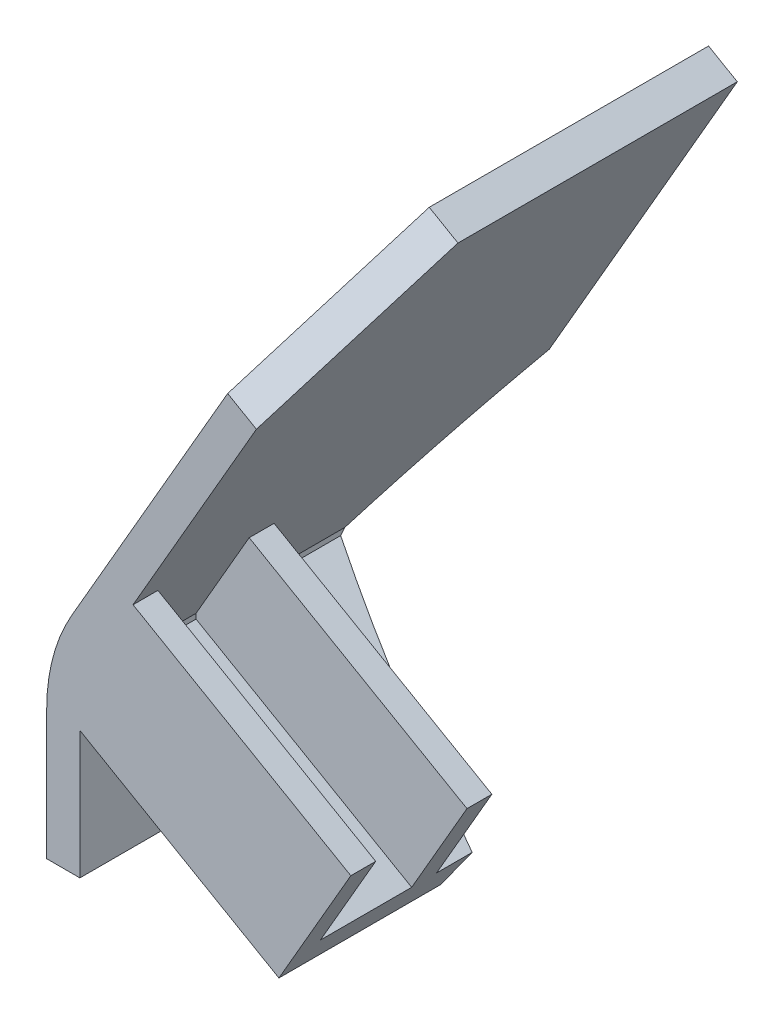
SolidWorks part; units mm, degrees
ref_plane "Alzado" through (0, 0, 0) normal (0, 0, 1) x (1, 0, 0)
ref_plane "Planta" through (0, 0, 0) normal (0, 1, 0) x (1, 0, 0)
ref_plane "Vista lateral" through (0, 0, 0) normal (1, 0, 0) x (0, 0, -1)
sketch "Croquis1" plane through (0, 0, 0) normal (0, 0, 1) x (1, 0, 0)
  line L0 (-23.0092, -16.2678) -> (-23.0092, 0)
  line L1 (-23.0092, 0) -> (5.7228, 49.7654)
  line L9 (-20.0092, -0.8038) -> (7.4549, 46.7654)
  line L16 (-20.0092, -16.2678) -> (-20.0092, -0.8038)
  line L17 (2.2587, 55.7654) -> (-29.0092, 1.6077) construction
  line L18 (26.9908, 55.7654) -> (2.2587, 55.7654) construction
  line L19 (26.9908, 46.7654) -> (26.9908, 55.7654) construction
  line L20 (-29.0092, 1.6077) -> (-29.0092, -70.1962) construction
  line L21 (-29.0092, -70.1962) -> (-20.0092, -70.1962) construction
  line L22 (-20.0092, -16.2678) -> (-23.0092, -16.2678)
  line L23 (-26.0092, 0.8038) -> (-26.0092, -67.1962) construction
  line L24 (-23.0092, -67.1962) -> (-23.0092, 0) construction
  line L25 (-20.0092, -70.1962) -> (-20.0092, -0.8038) construction
  line L26 (-26.0092, -67.1962) -> (-23.0092, -67.1962) construction
  line L27 (3.9908, 52.7654) -> (-26.0092, 0.8038) construction
  line L28 (23.9908, 52.7654) -> (3.9908, 52.7654) construction
  line L29 (23.9908, 49.7654) -> (23.9908, 52.7654) construction
  line L30 (7.4549, 46.7654) -> (5.7228, 49.7654)
  line L32 (5.7228, 49.7654) -> (23.9908, 49.7654) construction
  line L33 (7.4549, 46.7654) -> (26.9908, 46.7654) construction
  dimension "D2" = 20.0092
  dimension "D3" = 54.9282
  dimension "D4" = 57.4641
  dimension "D5" = 46.7654
  dimension "D1" = 3
extrude "Saliente-Extruir1" add sketch "Croquis1" along normal mid plane 36
fillet "Redondeo1" radius 17 1 edges at (-23.0092, 0, 0)
ref_plane "Plano1" through (-12.0465, -20.8651, 0) normal (0.5, 0.866, 0) x (0, 0, -1)
sketch "Croquis3" plane through (-20.0092, 0, 0) normal (1, 0, 0) x (0, 0, -1)
  line L1 (-18, -13.2678) -> (18, -13.2678)
  line L2 (-18, -13.2678) -> (-18, -16.2678)
  line L3 (-18, -16.2678) -> (18, -16.2678)
  line L4 (18, -13.2678) -> (18, -16.2678)
  line L5 (-18, -16.2678) -> (18, -16.2678) construction
  line L6 (-18, -16.2678) -> (-18, -0.8038) construction
  line L7 (18, -16.2678) -> (18, -0.8038) construction
  dimension "D1" = 3
extrude "Saliente-Extruir3" [suppressed] add sketch "Croquis3" along normal blind 10
ref_plane "Plano2" through (-7.9627, 4.5973, 0) normal (0.866, -0.5, 0) x (0, 0, -1)
sketch "Croquis5" plane through (-7.9627, 4.5973, 0) normal (0.866, -0.5, 0) x (0, 0, -1)
  line L1 (-18, -14.093) -> (18, -14.093)
  line L2 (-18, -14.093) -> (-18, -11.093)
  line L3 (-18, -11.093) -> (18, -11.093)
  line L4 (18, -14.093) -> (18, -11.093)
  line L5 (8.5052, -24.093) -> (-8.5052, -24.093) construction
  line L6 (-18, -24.093) -> (-18, -10.7008) construction
  point P10 (0, 0)
  dimension "D1" = 3
  dimension "D2" = 10
extrude "Saliente-Extruir4" add sketch "Croquis5" along normal blind 15 separate body
sketch "Croquis6" plane through (-5.5465, -9.6068, 0) normal (0.5, 0.866, 0) x (0.866, -0.5, 0)
  line L0 (-9.1946, -19.8) -> (-9.1946, 19.8) construction
  line L1 (5.8054, -18) -> (-9.1946, -18)
  line L2 (5.8054, -18) -> (5.8054, -15.75)
  line L3 (5.8054, -15.75) -> (-9.1946, -15.75)
  line L4 (-9.1946, -18) -> (-9.1946, -15.75)
  dimension "D1" = 2.25
extrude "Saliente-Extruir5" add sketch "Croquis6" along normal blind 10
sketch "Croquis7" plane through (-5.5465, -9.6068, 0) normal (0.5, 0.866, 0) x (0.866, -0.5, 0)
  line L0 (-9.1946, -19.8) -> (-9.1946, 19.8) construction
  line L1 (-9.1946, -5.25) -> (5.8054, -5.25)
  line L2 (-9.1946, -5.25) -> (-9.1946, -7.5)
  line L3 (-9.1946, -7.5) -> (5.8054, -7.5)
  line L4 (5.8054, -5.25) -> (5.8054, -7.5)
  line L5 (5.8054, 18) -> (5.8054, -15.75) construction
  line L6 (-9.1946, -18) -> (5.8054, -18) construction
  dimension "D1" = 10.5
  dimension "D2" = 2.25
extrude "Saliente-Extruir6" add sketch "Croquis7" along normal blind 10
sketch "Croquis8" plane through (-7.9627, 4.5973, 0) normal (-0.866, 0.5, 0) x (0, 0, 1)
  line L10 (18, -14.093) -> (18, -1.093)
  line L11 (18, -1.093) -> (15.75, -1.093)
  line L12 (15.75, -1.093) -> (15.75, -11.093)
  line L13 (15.75, -11.093) -> (7.5, -11.093)
  line L14 (7.5, -11.093) -> (7.5, -1.093)
  line L15 (7.5, -1.093) -> (5.25, -1.093)
  line L16 (5.25, -1.093) -> (5.25, -11.093)
  line L17 (5.25, -11.093) -> (-18, -11.093)
  line L18 (-18, -11.093) -> (-18, -14.093)
  line L19 (-18, -14.093) -> (18, -14.093)
  line L20 (18, -14.093) -> (18, -1.093)
  line L21 (18, -1.093) -> (15.75, -1.093)
  line L22 (15.75, -1.093) -> (15.75, -11.093)
  line L23 (15.75, -11.093) -> (7.5, -11.093)
  line L24 (7.5, -11.093) -> (7.5, -1.093)
  line L25 (7.5, -1.093) -> (5.25, -1.093)
  line L26 (5.25, -1.093) -> (5.25, -11.093)
  line L27 (5.25, -11.093) -> (-18, -11.093)
  line L28 (-18, -11.093) -> (-18, -14.093)
  line L29 (-18, -14.093) -> (18, -14.093)
  dimension "D1" = 0
extrude "Saliente-Extruir7" add sketch "Croquis8" along normal up to next
ref_plane "Plano3" through (0, 41.27, 0) normal (0, 1, 0) x (1, 0, 0)
sketch "Croquis9" plane through (0, 41.27, 0) normal (0, 1, 0) x (1, 0, 0)
  line L1 (-6.6606, 18.8519) -> (8.1435, 18.8519)
  line L2 (-6.6606, 18.8519) -> (-6.6606, -18.5663)
  line L3 (-6.6606, -18.5663) -> (8.1435, -18.5663)
  line L4 (8.1435, 18.8519) -> (8.1435, -18.5663)
extrude "Cortar-Extruir1" cut sketch "Croquis9" along normal through all
fillet "Redondeo2" [suppressed] radius 17
sketch "Croquis11" plane through (-17.2569, 9.9633, 0) normal (-0.866, 0.5, 0) x (0, 0, 1)
  line L0 (8.7886, 36.1499) -> (18, 36.1499)
  line L1 (-18, 36.1499) -> (18, 36.1499) construction
  line L2 (18, 36.1499) -> (18, 23.3515)
  line L3 (18, 36.1499) -> (18, -6.9495) construction
  line L4 (18, 23.3515) -> (8.7886, 36.1499)
  point P4 (0, 0)
  point P5 (0, 0)
  point P9 (0, 0)
  dimension "D1" = 35.744
extrude "Cortar-Extruir2" cut sketch "Croquis11" against normal through all
ref_plane "Plano5" through (18.0749, 31.3067, 0) normal (-0.5, -0.866, 0) x (-0.866, 0.5, 0)
sketch "Croquis13" plane through (18.0749, 31.3067, 0) normal (-0.5, -0.866, 0) x (-0.866, 0.5, 0)
  line L1 (21.2633, 19.0717) -> (14.4812, 19.0717)
  line L2 (21.2633, 19.0717) -> (21.2633, -18.979)
  line L3 (21.2633, -18.979) -> (14.4812, -18.979)
  line L4 (14.4812, 19.0717) -> (14.4812, -18.979)
extrude "Cortar-Extruir4" cut sketch "Croquis13" against normal through all
fillet "Redondeo6" [suppressed] radius 1
fillet "Redondeo4" [suppressed] radius 1
fillet "Redondeo7" [suppressed] radius 1
ref_plane "Plano6" through (7.8863, 13.6595, 21.9147) normal (0.2921, 0.5059, 0.8116) x (0.9564, -0.1545, -0.2479)
sketch "Croquis14" plane through (7.8863, 13.6595, 21.9147) normal (0.2921, 0.5059, 0.8116) x (0.9564, -0.1545, -0.2479)
  line L12 (-2.9215, 29.4526) -> (-8.7006, 32.1607)
  line L13 (-8.7006, 32.1607) -> (-16.6978, 15.0946)
  line L14 (-16.6978, 15.0946) -> (-10.9187, 12.3865)
  line L15 (-10.9187, 12.3865) -> (-2.9215, 29.4526)
  point P4 (0, 0)
extrude "Cortar-Extruir5" cut sketch "Croquis14" along normal through all
sketch "Croquis15" plane through (-23.0092, 0, 0) normal (-1, 0, 0) x (0, 0, 1)
  circle A0 centre (-57.4228, -44.4746) radius 67.5
  dimension "D1" = 135
extrude "Cortar-Extruir6" cut sketch "Croquis15" against normal through all
